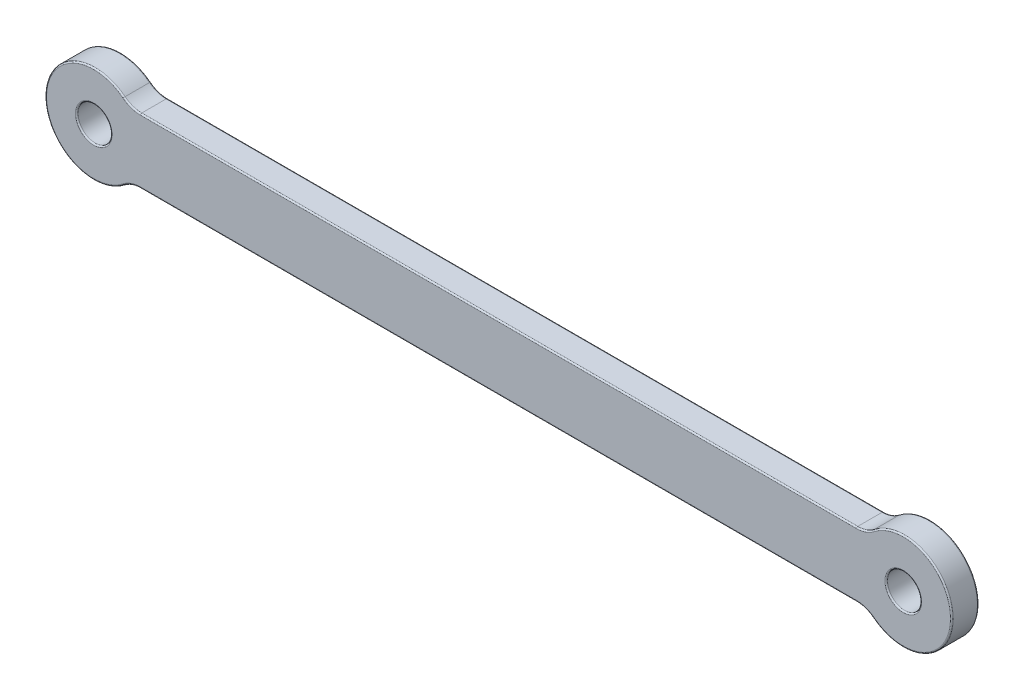
SolidWorks part; units mm, degrees
ref_plane "Front Plane" through (0, 0, 0) normal (0, 0, 1) x (1, 0, 0)
ref_plane "Top Plane" through (0, 0, 0) normal (0, 1, 0) x (1, 0, 0)
ref_plane "Right Plane" through (0, 0, 0) normal (1, 0, 0) x (0, 0, -1)
sketch "Sketch1" plane through (0, 0, 0) normal (0, 0, 1) x (1, 0, 0)
  line L0 (0, 0) -> (150, 0) construction
  line L1 (0, 9) -> (150, 9) construction
  line L2 (0, -9) -> (150, -9) construction
  line L3 (75, 0) -> (75, -9)
  line L5 (6.7082, -6) -> (143.2918, -6)
  line L6 (6.7082, -6) -> (6.7082, 6) construction
  line L7 (6.7082, 6) -> (143.2918, 6)
  line L8 (143.2918, -6) -> (143.2918, 6) construction
  line L9 (6.7082, -6) -> (143.2918, 6) construction
  line L10 (6.7082, 6) -> (143.2918, -6) construction
  arc A0 (0, 9) -> (0, -9) centre (0, 0) ccw construction
  arc A1 (150, -9) -> (150, 9) centre (150, 0) ccw construction
  circle A2 centre (0, 0) radius 3.15
  circle A3 centre (0, 0) radius 9
  circle A4 centre (150, 0) radius 3.15
  circle A5 centre (150, 0) radius 9
  point P3 (75, 0)
  dimension "D2" = 9
  dimension "D3" = 6.3
  dimension "D1" = 150
  dimension "D4" = 12
extrude "Boss-Extrude2" add sketch "Sketch1" along normal blind 5
fillet "Fillet1" radius 5 4 edges at (6.7082, -6, 2.5) (143.2918, -6, 2.5) (143.2918, 6, 2.5) (6.7082, 6, 2.5)
fillet "Fillet2" radius 0.25 20 edges at (3.15, 0, 5) (3.15, 0, 0) (153.15, 0, 5) (153.15, 0, 0) (7.0236, 6.2754, 5) (7.0236, 6.2754, 0) (-9, 0, 0) (-9, 0, 5) (7.0236, -6.2754, 5) (7.0236, -6.2754, 0) (75, -6, 5) (75, -6, 0) (142.9764, -6.2754, 5) (142.9764, -6.2754, 0) (159, 0, 5) (159, 0, 0) (142.9764, 6.2754, 5) (142.9764, 6.2754, 0) (75, 6, 5) (75, 6, 0)
